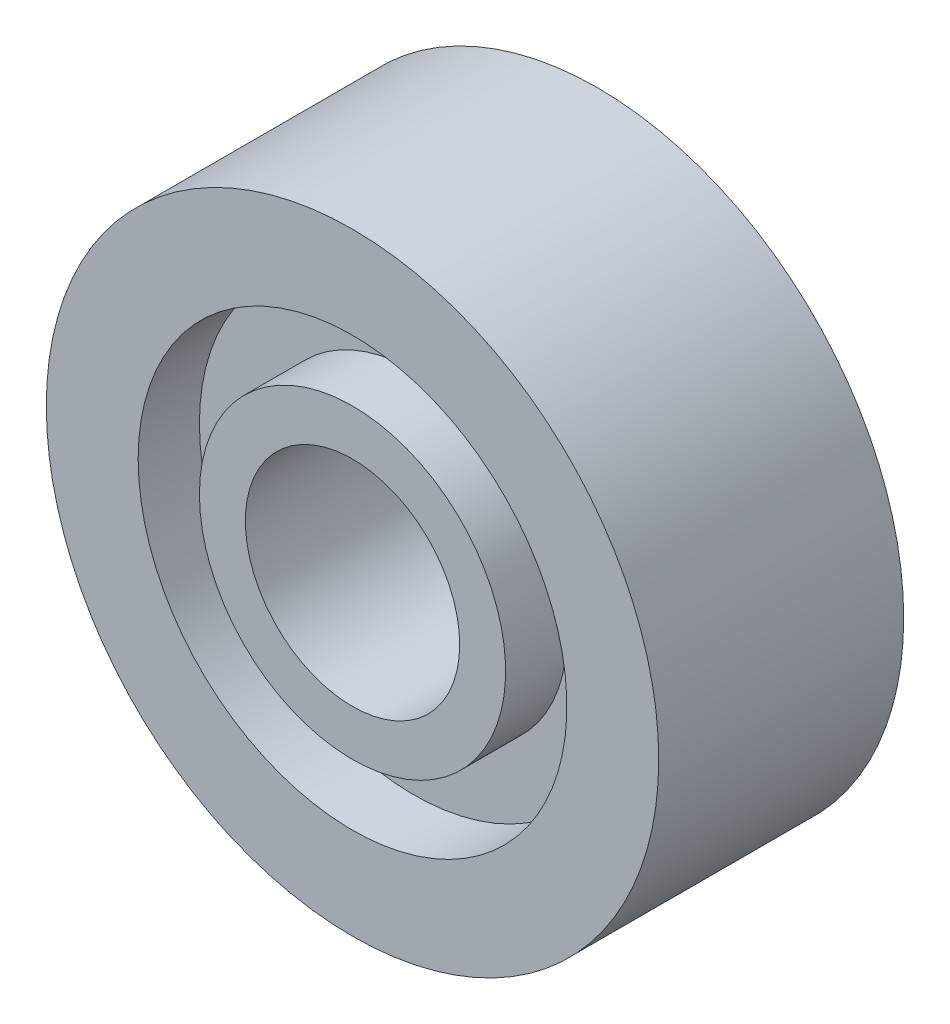
SolidWorks part; units mm, degrees
material "Хромистая нержавеющая сталь"
ref_plane "Спереди" through (0, 0, 0) normal (0, 0, 1) x (1, 0, 0)
ref_plane "Сверху" through (0, 0, 0) normal (0, 1, 0) x (1, 0, 0)
ref_plane "Справа" through (0, 0, 0) normal (1, 0, 0) x (0, 0, -1)
sketch "Эскиз1" plane through (0, 0, 0) normal (0, 0, 1) x (1, 0, 0)
  circle A0 centre (0, 0) radius 5
  circle A1 centre (0, 0) radius 1.75
  dimension "D1" = 10
  dimension "D2" = 3.5
extrude "Бобышка-Вытянуть1" add sketch "Эскиз1" along normal blind 4
ref_plane "Плоскость4" through (0, 0, 2) normal (0, 0, -1) x (-1, 0, 0)
sketch "Эскиз2" plane through (0, 0, 0) normal (0, 0, -1) x (-1, 0, 0)
  circle A0 centre (0, 0) radius 3.5
  circle A1 centre (0, 0) radius 2.5
  circle A2 centre (0, 0) radius 5 construction
  dimension "D1" = 1.5
  dimension "D2" = 1
extrude "Вырез-Вытянуть1" cut sketch "Эскиз2" against normal blind 1
mirror "Зеркальное отражение1" about plane through (0, 0, 2) normal (0, 0, -1) of "Вырез-Вытянуть1"
